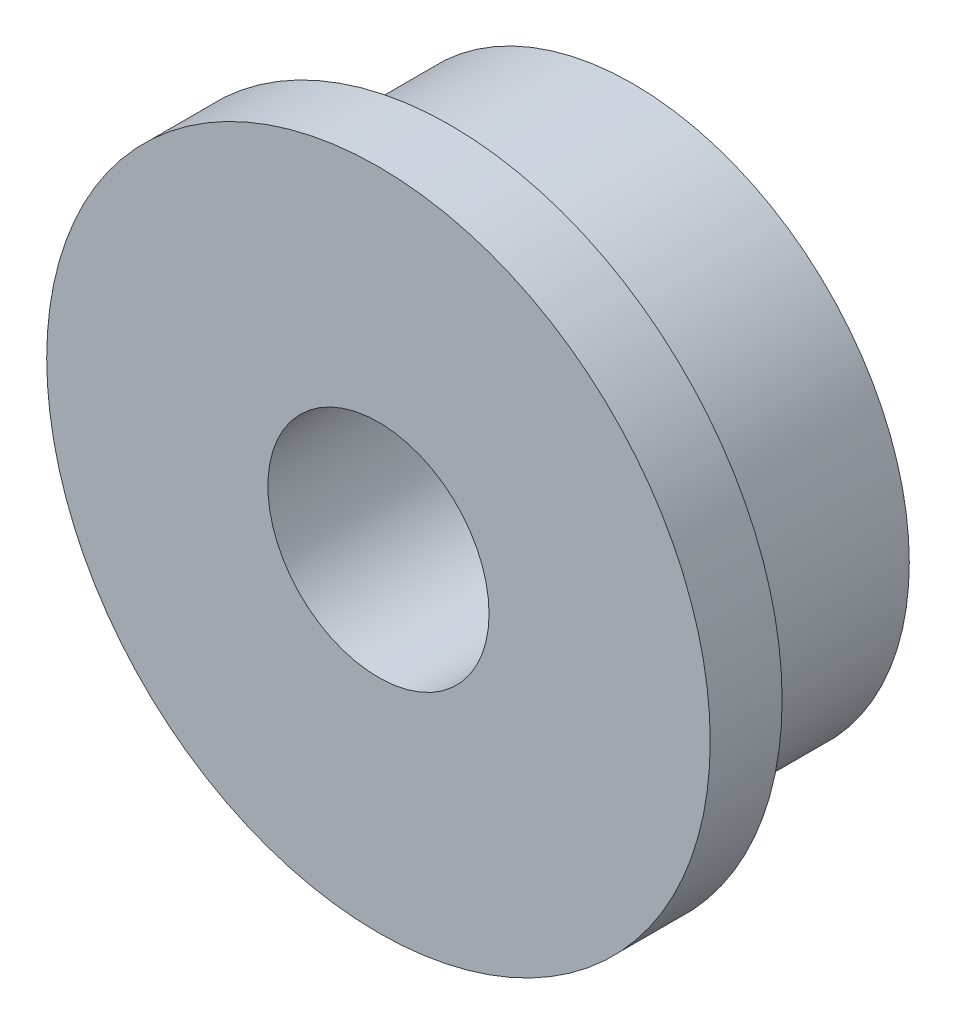
SolidWorks part; units mm, degrees
ref_plane "Front Plane" through (0, 0, 0) normal (0, 0, 1) x (1, 0, 0)
ref_plane "Top Plane" through (0, 0, 0) normal (0, 1, 0) x (1, 0, 0)
ref_plane "Right Plane" through (0, 0, 0) normal (1, 0, 0) x (0, 0, -1)
sketch "Sketch1" plane through (0, 0, 0) normal (0, 0, 1) x (1, 0, 0)
  circle A0 centre (0, 0) radius 1
  circle A1 centre (0, 0) radius 2.5
  dimension "D1" = 2
  dimension "D2" = 5
extrude "Boss-Extrude1" add sketch "Sketch1" along normal blind 1.65
sketch "Sketch2" plane through (0, 0, 1.65) normal (0, 0, 1) x (1, 0, 0)
  circle A0 centre (0, 0) radius 1
  circle A1 centre (0, 0) radius 3
  dimension "D1" = 6
  dimension "D2" = 2
extrude "Boss-Extrude2" add sketch "Sketch2" along normal blind 0.65
